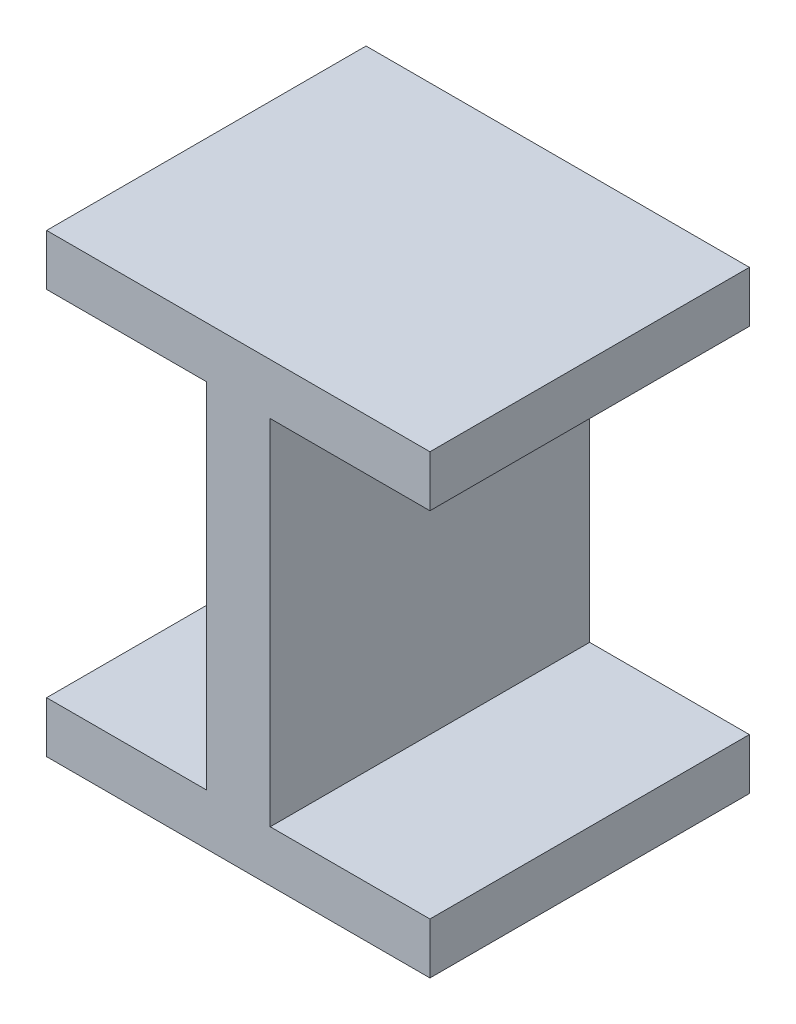
SolidWorks part; units mm, degrees
ref_plane "Front Plane" through (0, 0, 0) normal (0, 0, 1) x (1, 0, 0)
ref_plane "Top Plane" through (0, 0, 0) normal (0, 1, 0) x (1, 0, 0)
ref_plane "Right Plane" through (0, 0, 0) normal (1, 0, 0) x (0, 0, -1)
sketch "Sketch1" plane through (0, 0, 0) normal (0, 0, 1) x (1, 0, 0)
  line L1 (-5, 27.6691) -> (-30, 27.6691)
  line L2 (-30, 27.6691) -> (-30, 35.6691)
  line L3 (-30, 35.6691) -> (30, 35.6691)
  line L4 (-5, 27.6691) -> (-5, -27.6691)
  line L5 (5, -27.6691) -> (5, 27.6691)
  line L6 (30, 27.6691) -> (30, 35.6691)
  line L7 (5, 27.6691) -> (30, 27.6691)
  line L10 (-5, 27.6691) -> (-30, 27.6691)
  line L11 (-30, 27.6691) -> (-30, 35.6691)
  line L12 (30, 27.6691) -> (30, 35.6691)
  line L13 (5, 27.6691) -> (30, 27.6691)
  line L16 (5, -27.6691) -> (30, -27.6691)
  line L17 (30, -27.6691) -> (30, -35.6691)
  line L18 (-30, -27.6691) -> (-30, -35.6691)
  line L19 (-5, -27.6691) -> (-30, -27.6691)
  line L20 (5, -27.6691) -> (30, -27.6691)
  line L21 (30, -27.6691) -> (30, -35.6691)
  line L22 (-30, -35.6691) -> (30, -35.6691)
  line L23 (-30, -27.6691) -> (-30, -35.6691)
  line L24 (-5, -27.6691) -> (-30, -27.6691)
  point P12 (-5, 0)
  point P21 (5, 0)
  dimension "D2" = 8
extrude "Boss-Extrude1" add sketch "Sketch1" along normal blind 50 contours L18 L22 L17 L16 L5 L7 L6 L3 L2 L1 L4 L19
